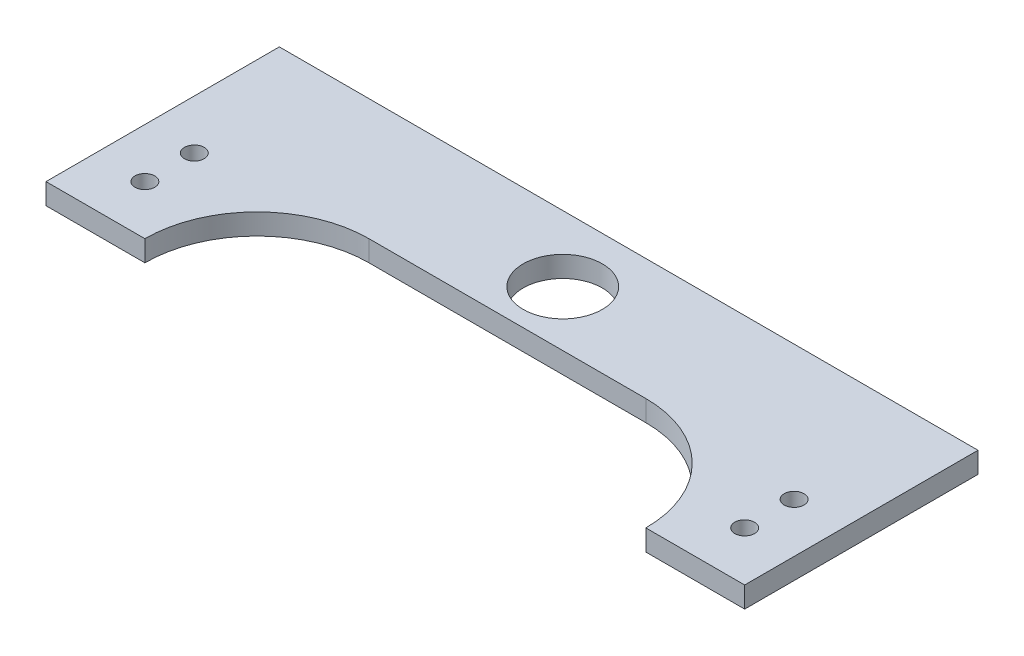
SolidWorks part; units mm, degrees
material "Cast Alloy Steel"
ref_plane "Front Plane" through (0, 0, 0) normal (0, 0, 1) x (1, 0, 0)
ref_plane "Top Plane" through (0, 0, 0) normal (0, 1, 0) x (1, 0, 0)
ref_plane "Right Plane" through (0, 0, 0) normal (1, 0, 0) x (0, 0, -1)
sketch "Sketch1" plane through (0, 0, 0) normal (0, 1, 0) x (1, 0, 0)
  line L0 (53, 0) -> (53, 25.4)
  line L1 (0, 0) -> (106, 0)
  line L2 (0, 0) -> (0, 50.8)
  line L3 (0, 50.8) -> (106, 50.8)
  line L4 (106, 0) -> (106, 50.8)
  line L5 (0, 0) -> (15, 0)
  line L6 (106, 0) -> (91, 0)
  line L7 (53, 19.4) -> (53, 17.4)
  line L12 (15, 0) -> (91, 0)
  line L13 (15, 0) -> (15, 17)
  line L14 (91, 0) -> (91, 17)
  line L15 (15, 17) -> (91, 17)
  line L16 (53, 31.4) -> (53, 35.4)
  line L17 (53, 35.4) -> (106, 35.4)
  line L18 (53, 35.4) -> (0, 35.4)
  circle A0 centre (53, 25.4) radius 6
  circle A1 centre (91, 0) radius 17
  circle A2 centre (74, 0) radius 17
  circle A3 centre (15, 0) radius 17
  circle A4 centre (32, 0) radius 17
  dimension "D4" = 2
  dimension "D5" = 17
  dimension "D1" = 106
  dimension "D2" = 50.8
  dimension "D3" = 25.4
  dimension "D6" = 4
extrude "Boss-Extrude1" add sketch "Sketch1" along normal blind 3.175 contours A1 L4 L17 L16 A0 L0 L15 | L4 A1 L14 L1 | A2 L14 A1 | A2 A1 L15 | A3 L15 L0 A0 L16 L18 L2 | L13 A3 L2 L1 | A4 A3 L13 | A4 L15 A3
sketch "Sketch3" plane through (0, 0, 0) normal (0, -1, 0) x (1, 0, 0)
  line L0 (7.5, 0) -> (7.5, -30)
  line L1 (0, 0) -> (15, 0) construction
  line L2 (53, -31.4) -> (53, -19.4)
  circle A0 centre (7.5, -15) radius 7.5
  circle A1 centre (7.5, -22.5) radius 1.5
  circle A2 centre (7.5, -7.5) radius 1.5
  circle A3 centre (53, -25.4) radius 6 construction
  circle A4 centre (98.5, -7.5) radius 1.5
  circle A5 centre (98.5, -22.5) radius 1.5
  circle A6 centre (7.5, -15) radius 1.5
  circle A7 centre (98.5, -15) radius 1.5
  dimension "D1" = 30
extrude "Cut-Extrude2" cut sketch "Sketch3" against normal through all contours L0 A6 | L0 A6 | A7 | A4 | A2
